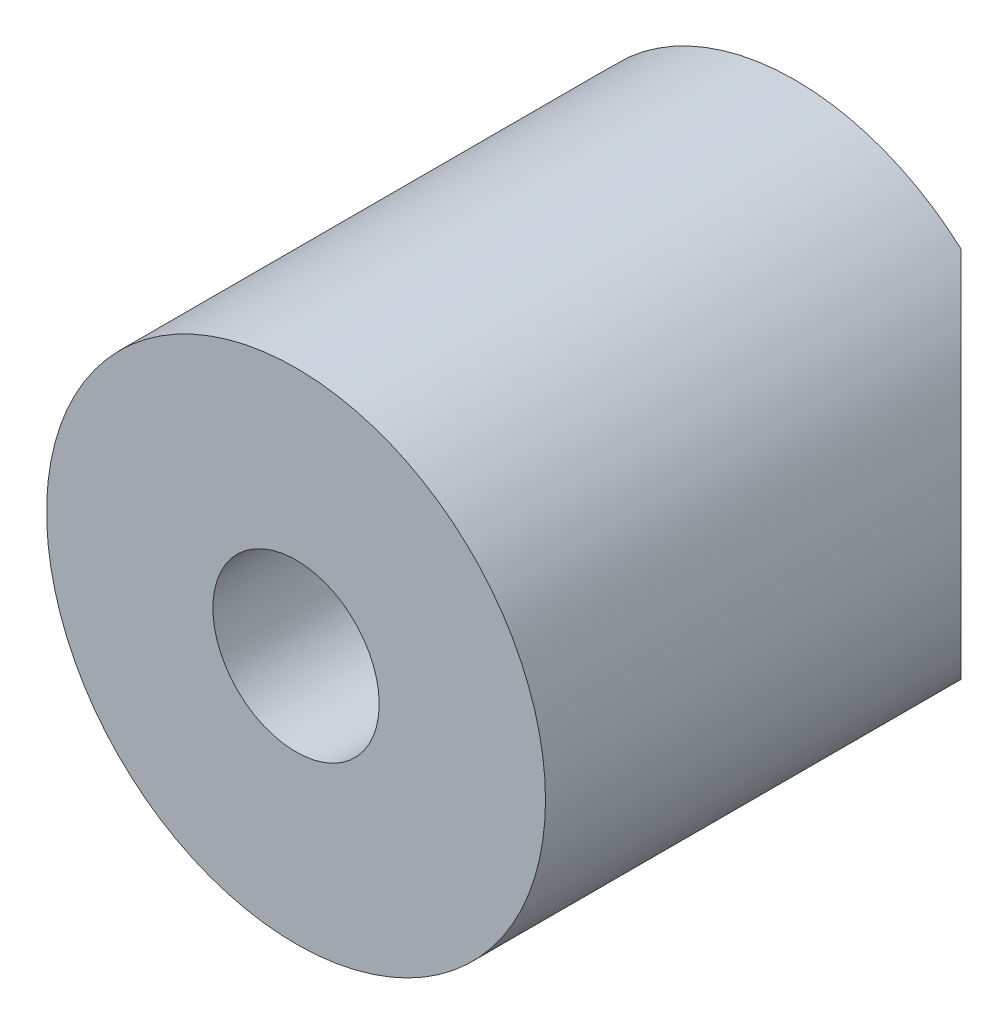
SolidWorks part; units mm, degrees
material "Ceramic Insulation"
ref_plane "Front Plane" through (0, 0, 0) normal (0, 0, 1) x (1, 0, 0)
ref_plane "Top Plane" through (0, 0, 0) normal (0, 1, 0) x (1, 0, 0)
ref_plane "Right Plane" through (0, 0, 0) normal (1, 0, 0) x (0, 0, -1)
sketch "Sketch1" plane through (0, 0, 0) normal (0, 0, 1) x (1, 0, 0)
  circle A0 centre (0, 0) radius 12.7
  circle A1 centre (0, 0) radius 38.1
  dimension "D2" = 25.4
  dimension "D1" = 25.4
extrude "Boss-Extrude1" add sketch "Sketch1" against normal blind 76.2
sketch "Sketch2" plane through (0, 0, 0) normal (0, 1, 0) x (1, 0, 0)
  line L0 (-25.4, 76.2) -> (-38.1, 63.5)
  line L1 (38.1, 76.2) -> (-38.1, 76.2) construction
  line L2 (-38.1, 63.5) -> (-38.1, 76.2)
  line L3 (-38.1, 76.2) -> (-38.1, 0) construction
  line L4 (-38.1, 76.2) -> (-25.4, 76.2)
  line L5 (0, 76.2) -> (0, 0) construction
  line L6 (38.1, 76.2) -> (25.4, 76.2)
  line L7 (38.1, 63.5) -> (38.1, 76.2)
  line L8 (25.4, 76.2) -> (38.1, 63.5)
  dimension "D1" = 12.7
  dimension "D2" = 45
extrude "Cut-Extrude1" cut sketch "Sketch2" against normal through all both and the other way through all
equation "\"ID\"= 1"
equation "\"D2@Sketch1\"=\"ID\""
equation "\"L\"= 4.5"
equation "\"D1@Boss-Extrude1\"=\"L\"-1.5"
equation "\"InsulationThickness\"= 1"
equation "\"D1@Sketch1\"=\"InsulationThickness\""
